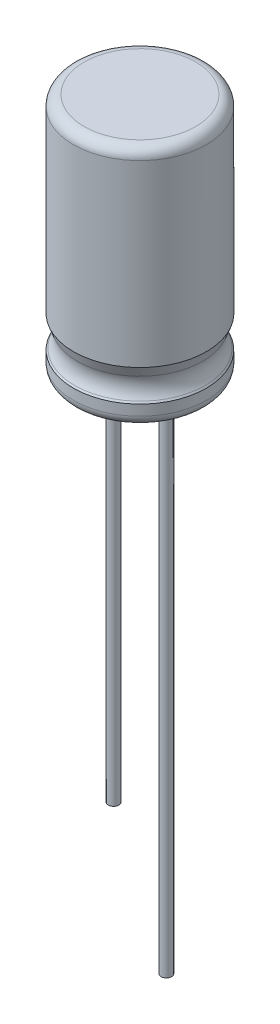
SolidWorks part; units mm, degrees
ref_plane "Alzado" through (0, 0, 0) normal (0, 0, 1) x (1, 0, 0)
ref_plane "Planta" through (0, 0, 0) normal (0, 1, 0) x (1, 0, 0)
ref_plane "Vista lateral" through (0, 0, 0) normal (1, 0, 0) x (0, 0, -1)
sketch "Croquis1" plane through (0, 0, 0) normal (0, 0, 1) x (1, 0, 0)
  line L1 (0, 0) -> (3.15, 0)
  line L2 (3.15, 0) -> (3.15, 1)
  line L3 (3.15, 2.5) -> (2.7818, 1.5138)
  line L4 (2.7818, 1.5138) -> (3.15, 1)
  line L5 (3.15, 2.5) -> (3.15, 11.5)
  line L6 (3.15, 11.5) -> (0, 11.5)
  line L7 (0, 11.5) -> (0, 0)
  point P6 (0, 0.1609)
  dimension "D1" = 3.15
  dimension "D4" = 11.5
  dimension "D5" = 1
  dimension "D6" = 1.5
revolve "Revolución1" add sketch "Croquis1" angle 360 about L7
fillet "Redondeo1" radius 1 1 edges at (0, 1.5138, 2.7818)
fillet "Redondeo2" radius 0.5 1 edges at (0, 11.5, 3.15)
fillet "Redondeo3" radius 0.5 1 edges at (0, 0, 3.15)
sketch "Croquis2" plane through (0, 0, 0) normal (0, -1, 0) x (1, 0, 0)
  line L0 (-0.85, 0.3) -> (0.85, 0.3)
  line L1 (0, 0) -> (1.3878, 0) construction
  line L2 (0, 1.75) -> (-3.1754, 1.75) construction
  line L3 (0, 0) -> (0, 1.0862) construction
  line L4 (-0.85, -0.3) -> (0.85, -0.3)
  circle A0 centre (0, 0) radius 1.75
  arc A1 (0.85, -0.3) -> (0.85, 0.3) centre (1.25, 0) ccw
  arc A2 (-0.85, -0.3) -> (-0.85, 0.3) centre (-1.25, 0) cw
  point P5 (0, 0.3)
  point P14 (0, 0)
  point P15 (0, 0)
  dimension "D1" = 3.5
  dimension "D4" = 1
  dimension "D2" = 0.3
  dimension "D5" = 1.25
extrude "Saliente-Extruir1" add sketch "Croquis2" along normal blind 0.2 separate body contours A0 A2 L0 A1 | L4 A2 A0 A1
ref_plane "Plano1" through (0, -24, 0) normal (0, 1, 0) x (1, 0, 0)
sketch "Croquis6" plane through (0, -24, 0) normal (0, 1, 0) x (1, 0, 0)
  circle A0 centre (1.25, 0) radius 0.25
  circle A1 centre (-1.25, 0) radius 0.25
  point P3 (-0.2081, -0.6779)
  dimension "D1" = 0.5
  dimension "D2" = 0.5
extrude "Saliente-Extruir16" add sketch "Croquis6" along normal blind 24 separate body
sketch "Croquis7" plane through (0, 0, 0) normal (0, 0, 1) x (1, 0, 0)
  line L0 (-1.5, -18.2) -> (-1, -18.2)
  line L1 (-1.5, 0) -> (-1.5, -24) construction
  line L2 (-1, -24) -> (-1, 0) construction
  line L3 (-1.75, -0.2) -> (1.75, -0.2) construction
  line L4 (-1.5, -18.2) -> (-1.5, -24)
  line L5 (-1.5, -24) -> (-1, -24)
  line L6 (-1, -24) -> (-1, -18.2)
  dimension "D1" = 18
extrude "Cortar-Extruir2" cut sketch "Croquis7" against normal blind 5 and the other way blind 5 contours L6 L0 L4 L5
